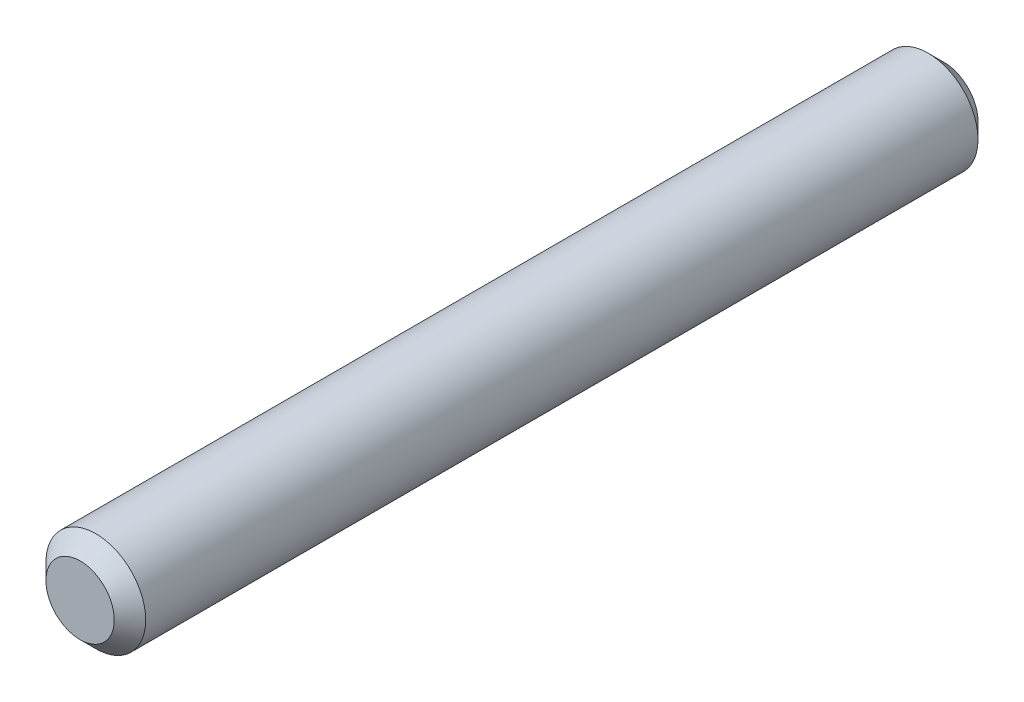
SolidWorks part; units mm, degrees
material "AISI 1020"
ref_plane "Front Plane" through (0, 0, 0) normal (0, 0, 1) x (1, 0, 0)
ref_plane "Top Plane" through (0, 0, 0) normal (0, 1, 0) x (1, 0, 0)
ref_plane "Right Plane" through (0, 0, 0) normal (1, 0, 0) x (0, 0, -1)
sketch "Sketch1" plane through (0, 0, 0) normal (0, 0, 1) x (1, 0, 0)
  circle A0 centre (0, 0) radius 3.175
  dimension "D1" = 6.35
extrude "Boss-Extrude1" add sketch "Sketch1" against normal blind 55
cosmetic thread "Cosmetic Thread1" parameters "D2"=4.8387
chamfer "Chamfer1" distance 1 angle 45 2 edges at (3.175, 0, -55) (3.175, 0, 0)
